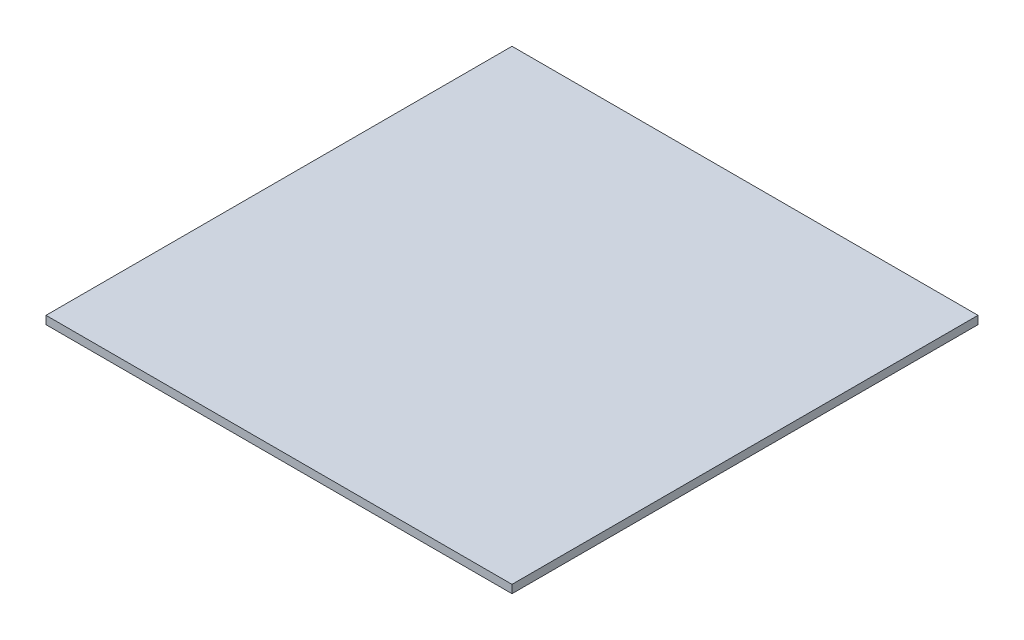
SolidWorks part; units mm, degrees
ref_plane "Front Plane" through (0, 0, 0) normal (0, 0, 1) x (1, 0, 0)
ref_plane "Top Plane" through (0, 0, 0) normal (0, 1, 0) x (1, 0, 0)
ref_plane "Right Plane" through (0, 0, 0) normal (1, 0, 0) x (0, 0, -1)
sketch "Sketch1" plane through (0, 0, 0) normal (0, 1, 0) x (1, 0, 0)
  line L1 (4300, -4300) -> (-4300, -4300)
  line L2 (4300, -4300) -> (4300, 4300)
  line L3 (4300, 4300) -> (-4300, 4300)
  line L4 (-4300, -4300) -> (-4300, 4300)
  line L5 (4300, -4300) -> (-4300, 4300) construction
  line L6 (4300, 4300) -> (-4300, -4300) construction
  point P0 (0, 0)
  dimension "D1" = 8600
  dimension "D2" = 8600
extrude "Boss-Extrude1" add sketch "Sketch1" along normal blind 150
